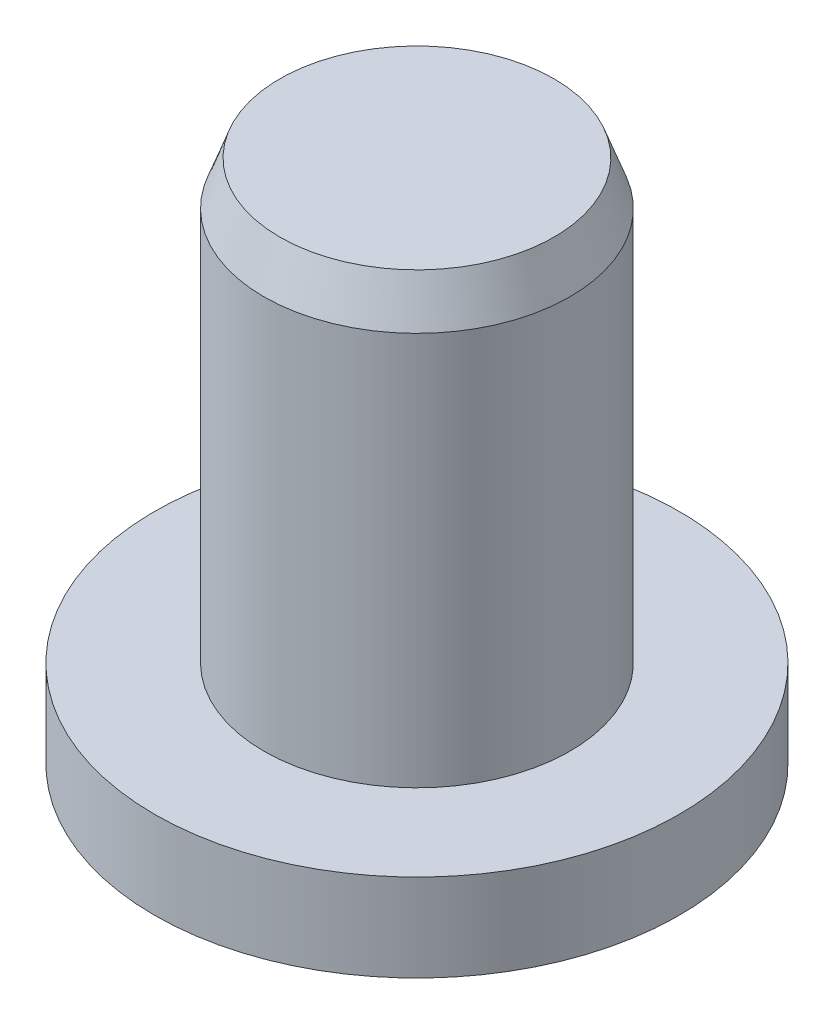
SolidWorks part; units mm, degrees
ref_plane "Front Plane" through (0, 0, 0) normal (0, 0, 1) x (1, 0, 0)
ref_plane "Top Plane" through (0, 0, 0) normal (0, 1, 0) x (1, 0, 0)
ref_plane "Right Plane" through (0, 0, 0) normal (1, 0, 0) x (0, 0, -1)
sketch "Sketch1" plane through (0, 0, 0) normal (0, 1, 0) x (1, 0, 0)
  circle A0 centre (0, 0) radius 6
  dimension "D1" = 12
extrude "Boss-Extrude1" add sketch "Sketch1" along normal blind 2
sketch "Sketch2" plane through (0, 2, 0) normal (0, 1, 0) x (1, 0, 0)
  circle A0 centre (0, 0) radius 3.5
  dimension "D1" = 7
extrude "Boss-Extrude2" add sketch "Sketch2" along normal blind 10
chamfer "Chamfer1" distance 1 angle 20 1 edges at (0, 12, 3.5)
